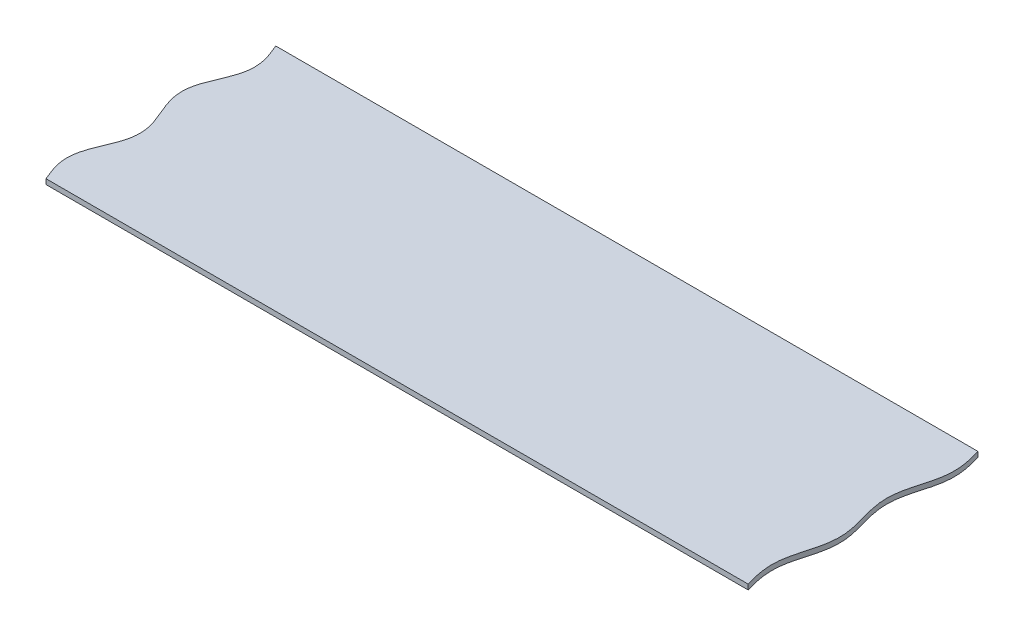
SolidWorks part; units mm, degrees
ref_plane "Front Plane" through (0, 0, 0) normal (0, 0, 1) x (1, 0, 0)
ref_plane "Top Plane" through (0, 0, 0) normal (0, 1, 0) x (1, 0, 0)
ref_plane "Right Plane" through (0, 0, 0) normal (1, 0, 0) x (0, 0, -1)
sketch "Sketch1" plane through (0, 0, 0) normal (0, 1, 0) x (1, 0, 0)
  line L0 (0, 0) -> (55, 0)
  line L2 (55, -18) -> (0, -18)
  spline S0 degree 4 poles (-0.5685, 1.7821) (-0.557, 1.6985) (-0.5295, 1.5323) (-0.4772, 1.2969) (-0.3953, 1.0229) (-0.3202, 0.8033) (-0.2254, 0.5446) (-0.03, 0.0672) (0.0329, -0.074) (0.2309, -0.5581) (0.314, -0.7865) (0.3626, -0.9275) (0.4246, -1.1203) (0.4923, -1.3616) (0.5544, -1.6497) (0.5923, -1.9494) (0.603, -2.2069) (0.5966, -2.4647) (0.5731, -2.7217) (0.5142, -3.064) (0.3993, -3.4853) (0.2509, -3.8957) (0.0855, -4.2992) (-0.0996, -4.7374) (-0.2968, -5.2207) (-0.4936, -5.797) (-0.619, -6.4834) (-0.5996, -7.2321) (-0.3812, -8.1201) (-0.0001, -9) (0.3813, -9.8798) (0.6005, -10.7677) (0.6207, -11.5162) (0.496, -12.2029) (0.2996, -12.7792) (0.1024, -13.2626) (-0.0827, -13.7009) (-0.2481, -14.1043) (-0.3967, -14.5146) (-0.5119, -14.9358) (-0.5785, -15.3205) (-0.6049, -15.6636) (-0.5963, -16.008) (-0.554, -16.3492) (-0.483, -16.6774) (-0.3929, -16.9881) (-0.2861, -17.2934) (-0.1847, -17.5561) (-0.038, -17.9103) (0.0361, -18.0854) (0.1804, -18.4332) (0.2814, -18.6932) (0.3864, -18.9903) (0.4768, -19.2947) (0.5304, -19.5328) (0.558, -19.6986) (0.5694, -19.782) knots 0 0 0 0 0 0.014933 0.029865 0.04323 0.049912 0.056594 0.083322 0.110605 0.117425 0.124246 0.131066 0.137887 0.153149 0.168412 0.183675 0.191306 0.198937 0.2142 0.229463 0.252929 0.276396 0.291658 0.306921 0.337447 0.369117 0.399642 0.430167 0.469469 0.53052 0.569821 0.600347 0.630872 0.662542 0.693068 0.70833 0.723593 0.747059 0.770526 0.785789 0.801051 0.816314 0.831577 0.846839 0.862102 0.875743 0.889384 0.903025 0.916666 0.930032 0.943398 0.956764 0.970131 0.985065 1 1 1 1 1 construction
  spline S1 degree 4 poles (0, 0) (0.0494, -0.118) (0.1111, -0.2653) (0.2309, -0.5581) (0.314, -0.7865) (0.3626, -0.9275) (0.4246, -1.1203) (0.4923, -1.3616) (0.5544, -1.6497) (0.5923, -1.9494) (0.603, -2.2069) (0.5966, -2.4647) (0.5731, -2.7217) (0.5142, -3.064) (0.3993, -3.4853) (0.2509, -3.8957) (0.0855, -4.2992) (-0.0996, -4.7374) (-0.2968, -5.2207) (-0.4936, -5.797) (-0.619, -6.4834) (-0.5996, -7.2321) (-0.3812, -8.1201) (-0.0001, -9) (0.3813, -9.8798) (0.6005, -10.7677) (0.6207, -11.5162) (0.496, -12.2029) (0.2996, -12.7792) (0.1024, -13.2626) (-0.0827, -13.7009) (-0.2481, -14.1043) (-0.3967, -14.5146) (-0.5119, -14.9358) (-0.5785, -15.3205) (-0.6049, -15.6636) (-0.5963, -16.008) (-0.554, -16.3492) (-0.483, -16.6774) (-0.3929, -16.9881) (-0.2861, -17.2934) (-0.1847, -17.5561) (-0.0741, -17.8231) (-0.0247, -17.941) (0, -18) knots 0.083322 0.083322 0.083322 0.083322 0.083322 0.110605 0.117425 0.124246 0.131066 0.137887 0.153149 0.168412 0.183675 0.191306 0.198937 0.2142 0.229463 0.252929 0.276396 0.291658 0.306921 0.337447 0.369117 0.399642 0.430167 0.469469 0.53052 0.569821 0.600347 0.630872 0.662542 0.693068 0.70833 0.723593 0.747059 0.770526 0.785789 0.801051 0.816314 0.831577 0.846839 0.862102 0.875743 0.889384 0.903025 0.916666 0.916666 0.916666 0.916666 0.916666
  spline S2 degree 4 poles (54.6208, 1.7828) (54.6288, 1.6982) (54.6475, 1.5307) (54.6798, 1.3049) (54.7471, 0.9747) (54.8154, 0.6715) (54.9717, 0.096) (55.0309, -0.1051) (55.1898, -0.691) (55.2579, -0.9977) (55.3257, -1.3363) (55.3689, -1.6489) (55.3989, -1.9945) (55.4039, -2.3311) (55.3876, -2.6724) (55.3445, -3.0512) (55.2696, -3.4693) (55.1512, -3.9642) (54.9904, -4.536) (54.8171, -5.1507) (54.6675, -5.8163) (54.5876, -6.495) (54.6004, -7.2231) (54.7421, -8.1087) (55.0025, -9.0079) (55.2617, -9.9075) (55.4013, -10.7905) (55.4129, -11.5139) (55.3327, -12.1901) (55.1836, -12.853) (55.0112, -13.4651) (54.8506, -14.0362) (54.732, -14.5306) (54.657, -14.9487) (54.6136, -15.3275) (54.5971, -15.6688) (54.6019, -16.0054) (54.6317, -16.351) (54.6746, -16.6636) (54.7423, -17.0022) (54.8103, -17.309) (54.9691, -17.8949) (55.0283, -18.0961) (55.1846, -18.6715) (55.2531, -18.9747) (55.3206, -19.3049) (55.353, -19.5307) (55.3718, -19.6982) (55.3798, -19.7828) knots 0 0 0 0 0 0.015175 0.030349 0.043501 0.056652 0.082955 0.109919 0.1234 0.136882 0.152331 0.16778 0.183228 0.198677 0.214125 0.229574 0.252676 0.275777 0.306674 0.337572 0.368827 0.399724 0.430621 0.469601 0.531395 0.569874 0.600771 0.631669 0.662566 0.693392 0.724218 0.747319 0.770421 0.785869 0.801318 0.816767 0.832215 0.847664 0.863112 0.876594 0.890076 0.91704 0.943344 0.956497 0.969649 0.984824 1 1 1 1 1 construction
  spline S3 degree 4 poles (55, 0) (55.0333, -0.1191) (55.083, -0.2972) (55.1898, -0.691) (55.2579, -0.9977) (55.3257, -1.3363) (55.3689, -1.6489) (55.3989, -1.9945) (55.4039, -2.3311) (55.3876, -2.6724) (55.3445, -3.0512) (55.2696, -3.4693) (55.1512, -3.9642) (54.9904, -4.536) (54.8171, -5.1507) (54.6675, -5.8163) (54.5876, -6.495) (54.6004, -7.2231) (54.7421, -8.1087) (55.0025, -9.0079) (55.2617, -9.9075) (55.4013, -10.7905) (55.4129, -11.5139) (55.3327, -12.1901) (55.1836, -12.853) (55.0112, -13.4651) (54.8506, -14.0362) (54.732, -14.5306) (54.657, -14.9487) (54.6136, -15.3275) (54.5971, -15.6688) (54.6019, -16.0054) (54.6317, -16.351) (54.6746, -16.6636) (54.7423, -17.0022) (54.8103, -17.309) (54.917, -17.7028) (54.9667, -17.8809) (55, -18) knots 0.082955 0.082955 0.082955 0.082955 0.082955 0.109919 0.1234 0.136882 0.152331 0.16778 0.183228 0.198677 0.214125 0.229574 0.252676 0.275777 0.306674 0.337572 0.368827 0.399724 0.430621 0.469601 0.531395 0.569874 0.600771 0.631669 0.662566 0.693392 0.724218 0.747319 0.770421 0.785869 0.801318 0.816767 0.832215 0.847664 0.863112 0.876594 0.890076 0.91704 0.91704 0.91704 0.91704 0.91704
  point P3 (55, -0.3308)
  point P4 (55, -18.3322)
  point P5 (55.0896, -18)
  dimension "D4" = 18
  dimension "D5" = 55
extrude "Boss-Extrude1" add sketch "Sketch1" along normal blind 0.4
